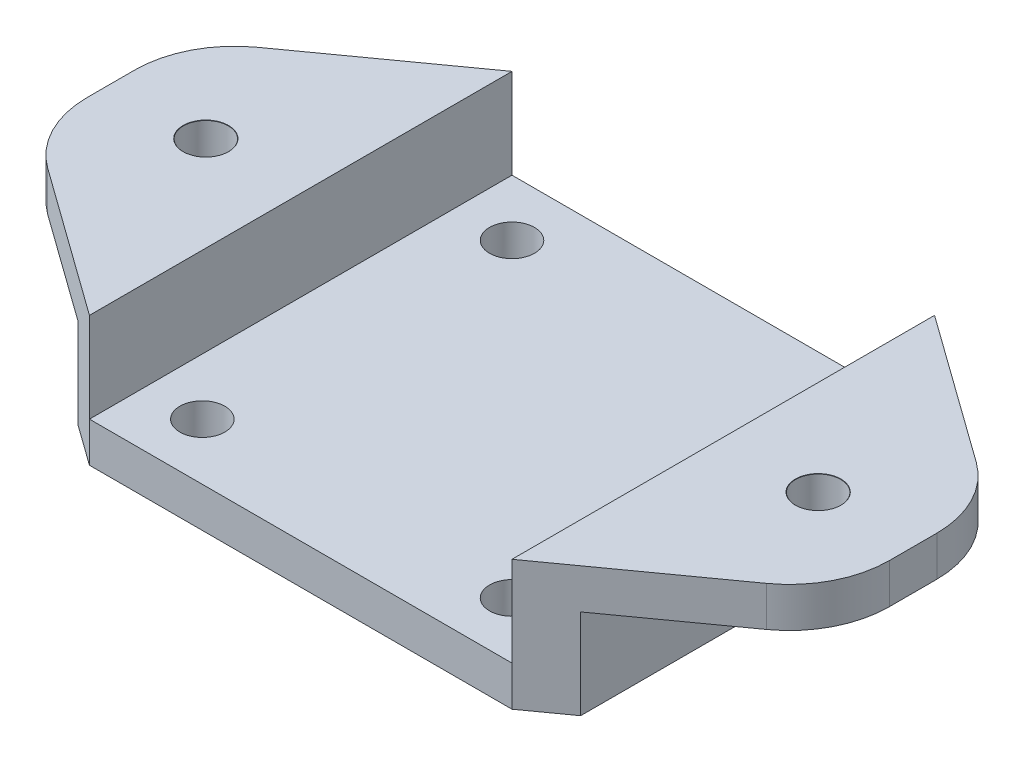
SolidWorks part; units mm, degrees
material "ABS"
ref_plane "Piano frontale" through (0, 0, 0) normal (0, 0, 1) x (1, 0, 0)
ref_plane "Piano superiore" through (0, 0, 0) normal (0, 1, 0) x (1, 0, 0)
ref_plane "Piano destro" through (0, 0, 0) normal (1, 0, 0) x (0, 0, -1)
sketch "Schizzo1" plane through (0, 0, 0) normal (0, 1, 0) x (1, 0, 0)
  line L1 (-25.15, -21.15) -> (25.15, -21.15)
  line L2 (-25.15, -21.15) -> (-25.15, 21.15)
  line L3 (-25.15, 21.15) -> (25.15, 21.15)
  line L4 (25.15, -21.15) -> (25.15, 21.15)
  line L5 (-25.15, -21.15) -> (25.15, 21.15) construction
  line L6 (-25.15, 21.15) -> (25.15, -21.15) construction
  point P0 (0, 0)
  point P5 (0, 0)
  dimension "D1" = 42.3
  dimension "D2" = 50.3
extrude "Estrusione-Estrusione1" add sketch "Schizzo1" along normal blind 4
sketch "Schizzo3" plane through (0, 0, 21.15) normal (0, 0, 1) x (1, 0, 0)
  line L0 (-21.15, 4) -> (-21.15, 13)
  line L1 (-25.15, 4) -> (25.15, 4) construction
  line L2 (-21.15, 13) -> (-40.15, 13)
  line L3 (-40.15, 13) -> (-40.15, 9)
  line L4 (-40.15, 9) -> (-25.15, 9)
  line L5 (-25.15, 9) -> (-25.15, 4)
  line L6 (-25.15, 4) -> (-21.15, 4)
  line L7 (25.15, 4) -> (25.15, 9)
  line L8 (25.15, 9) -> (40.15, 9)
  line L9 (40.15, 9) -> (40.15, 13)
  line L10 (40.15, 13) -> (21.15, 13)
  line L11 (21.15, 13) -> (21.15, 4)
  line L12 (21.15, 4) -> (25.15, 4)
  point P12 (18.7011, 23.546)
  dimension "D1" = 4
  dimension "D2" = 15
  dimension "D3" = 9
extrude "Estrusione-Estrusione2" add sketch "Schizzo3" against normal blind 42.3
sketch "Schizzo4" plane through (0, 4, 0) normal (0, 1, 0) x (1, 0, 0)
  line L1 (-15.5, -15.5) -> (15.5, -15.5) construction
  line L2 (-15.5, -15.5) -> (-15.5, 15.5) construction
  line L3 (-15.5, 15.5) -> (15.5, 15.5) construction
  line L4 (15.5, -15.5) -> (15.5, 15.5) construction
  line L5 (-15.5, -15.5) -> (15.5, 15.5) construction
  line L6 (-15.5, 15.5) -> (15.5, -15.5) construction
  circle A0 centre (-15.5, 15.5) radius 2.25
  circle A1 centre (15.5, 15.5) radius 2.25
  circle A2 centre (15.5, -15.5) radius 2.25
  circle A3 centre (-15.5, -15.5) radius 2.25
  point P0 (0, 0)
  dimension "D1" = 4.5
  dimension "D2" = 31
extrude "Taglio-Estrusione1" cut sketch "Schizzo4" against normal blind 42.3
hole_wizard "Foro per Vite M4-1" positions "Schizzo5" profile "Schizzo6" hole size "M4" standard "ISO"
sketch "Schizzo5" plane through (0, 13, 0) normal (0, 1, 0) x (1, 0, 0)
  line L0 (-30.65, 0) -> (30.65, 0) construction
  line L2 (-30.65, -21.15) -> (-30.65, 0) construction
  line L3 (-21.15, -21.15) -> (-40.15, -21.15) construction
  point P0 (-30.65, 0)
  point P2 (30.65, 0)
  point P9 (0, 0)
sketch "Schizzo6" plane through (-30.65, 13, 0) normal (1, 0, 0) x (0, 0, 1)
  line L0 (0, 0) -> (0, 5.3519)
  line L1 (0, 5.3519) -> (2.25, 4)
  line L2 (2.25, 4) -> (2.25, 0.025)
  line L3 (2.25, 0.025) -> (2.275, 0)
  line L5 (2.275, 0) -> (0, 0)
  line L6 (-2.25, 0.025) -> (-2.275, 0) construction
  line L10 (0, 5.3519) -> (-2.25, 4) construction
  line L11 (0, -6.35) -> (0, 107.95) construction
  dimension "Hole Dia." = 4.5
  dimension "Hole Depth" = 4
  dimension "Near C'Sink Dia." = 4.55
  dimension "Near C'Sink Angle" = 90
  dimension "Drill Angle" = 118
sketch "Schizzo7" plane through (0, 13, 0) normal (0, 1, 0) x (1, 0, 0)
  line L0 (-21.15, -21.15) -> (-40.15, -7.5)
  line L1 (-40.15, 21.15) -> (-40.15, -21.15) construction
  line L2 (-40.15, -7.5) -> (-40.15, -21.15)
  line L3 (-40.15, -21.15) -> (-21.15, -21.15)
  line L4 (-21.15, 21.15) -> (-40.15, 7.5)
  line L5 (-40.15, 7.5) -> (-40.15, 21.15)
  line L6 (-40.15, 21.15) -> (-21.15, 21.15)
  line L7 (21.15, 21.15) -> (40.15, 21.15)
  line L8 (40.15, 21.15) -> (40.15, 7.5)
  line L9 (40.15, 21.15) -> (40.15, -21.15) construction
  line L10 (40.15, 7.5) -> (21.15, 21.15)
  line L11 (21.15, -21.15) -> (40.15, -21.15)
  line L12 (40.15, -21.15) -> (40.15, -7.5)
  line L13 (40.15, -7.5) -> (21.15, -21.15)
  dimension "D1" = 15
extrude "Taglio-Estrusione2" cut sketch "Schizzo7" against normal blind 42.3
fillet "Raccordo1" radius 10 4 edges at (40.15, 11, -7.5) (40.15, 11, 7.5) (-40.15, 11, -7.5) (-40.15, 11, 7.5)
